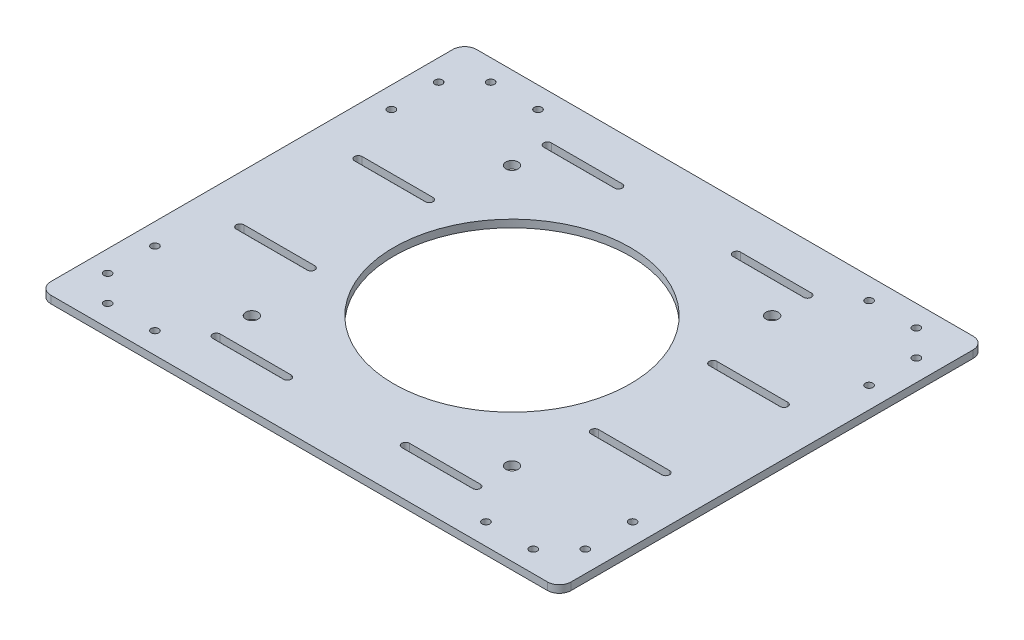
SolidWorks part; units mm, degrees
ref_plane "Front Plane" through (0, 0, 0) normal (0, 0, 1) x (1, 0, 0)
ref_plane "Top Plane" through (0, 0, 0) normal (0, 1, 0) x (1, 0, 0)
ref_plane "Right Plane" through (0, 0, 0) normal (1, 0, 0) x (0, 0, -1)
sketch "Sketch1" plane through (0, 0, 0) normal (0, 1, 0) x (1, 0, 0)
  line L1 (110, -90) -> (-110, -90)
  line L2 (110, -90) -> (110, 90)
  line L3 (110, 90) -> (-110, 90)
  line L4 (-110, -90) -> (-110, 90)
  line L5 (110, -90) -> (-110, 90) construction
  line L6 (110, 90) -> (-110, -90) construction
  point P0 (0, 0)
  dimension "D1" = 220
  dimension "D2" = 180
extrude "Boss-Extrude1" add sketch "Sketch1" along normal blind 3.175
fillet "Fillet1" radius 5 4 edges at (-110, 1.5875, 90) (110, 1.5875, 90) (110, 1.5875, -90) (-110, 1.5875, -90)
sketch "Sketch2" plane through (0, 3.175, 0) normal (0, 1, 0) x (1, 0, 0)
  circle A0 centre (0, 0) radius 69 construction
  circle A1 centre (0, 0) radius 50
  dimension "D1" = 138
  dimension "D2" = 100
extrude "Cut-Extrude1" cut sketch "Sketch2" against normal blind 10
sketch "Sketch4" plane through (0, 3.175, 0) normal (0, 1, 0) x (1, 0, 0)
  line L0 (-90, 81) -> (-70, 81) construction
  line L1 (-90, 84) -> (-70, 84) construction
  line L2 (-90, 78) -> (-70, 78) construction
  line L4 (-110, 85) -> (-110, -85) construction
  line L5 (105, 90) -> (-105, 90) construction
  line L6 (-101, 70) -> (-101, 50) construction
  line L7 (-98, 70) -> (-98, 50) construction
  line L8 (-104, 70) -> (-104, 50) construction
  arc A0 (-90, 84) -> (-90, 78) centre (-90, 81) ccw construction
  arc A1 (-70, 78) -> (-70, 84) centre (-70, 81) ccw construction
  arc A2 (-98, 70) -> (-104, 70) centre (-101, 70) ccw construction
  arc A3 (-104, 50) -> (-98, 50) centre (-101, 50) ccw construction
  point P2 (-80, 81)
  point P13 (-101, 60)
  dimension "D1" = 6
  dimension "D2" = 20
  dimension "D3" = 30
  dimension "D4" = 9
  dimension "D5" = 20
  dimension "D6" = 30
  dimension "D7" = 6
  dimension "D8" = 9
sketch "Sketch5" plane through (0, 3.175, 0) normal (0, 1, 0) x (1, 0, 0)
  circle A0 centre (-70, 81) radius 1.6
  circle A1 centre (-90, 81) radius 1.6
  circle A2 centre (-101, 70) radius 1.6
  circle A3 centre (-101, 50) radius 1.6
  dimension "D1" = 3.2
extrude "Cut-Extrude3" cut sketch "Sketch5" against normal blind 10
mirror "Mirror1" about plane through (0, 0, 0) normal (1, 0, 0) of "Cut-Extrude3"
mirror "Mirror2" about plane through (0, 0, 0) normal (0, 0, 1) of "Mirror1", "Cut-Extrude3"
sketch "Sketch6" plane through (0, 3.175, 0) normal (0, 1, 0) x (1, 0, 0)
  line L1 (55, -55) -> (-55, -55) construction
  line L2 (55, -55) -> (55, 55) construction
  line L3 (55, 55) -> (-55, 55) construction
  line L4 (-55, -55) -> (-55, 55) construction
  line L5 (55, -55) -> (-55, 55) construction
  line L6 (55, 55) -> (-55, -55) construction
  point P0 (0, 0)
  dimension "D1" = 110
  dimension "D2" = 110
sketch "Sketch7" plane through (0, 3.175, 0) normal (0, 1, 0) x (1, 0, 0)
  circle A0 centre (-55, 55) radius 2.6
  circle A1 centre (55, 55) radius 2.6
  circle A2 centre (55, -55) radius 2.6
  circle A3 centre (-55, -55) radius 2.6
  dimension "D1" = 5.2
extrude "Cut-Extrude4" cut sketch "Sketch7" against normal blind 10
sketch "Sketch8" plane through (0, 3.175, 0) normal (0, 1, 0) x (1, 0, 0)
  line L1 (-40, -70) -> (40, -70) construction
  line L2 (-40, -70) -> (-40, 70) construction
  line L3 (-40, 70) -> (40, 70) construction
  line L4 (40, -70) -> (40, 70) construction
  line L5 (-40, -70) -> (40, 70) construction
  line L6 (-40, 70) -> (40, -70) construction
  line L7 (105, 90) -> (-105, 90) construction
  line L8 (-55, 70) -> (-25, 70) construction
  line L9 (-55, 71.6) -> (-25, 71.6)
  line L10 (-55, 68.4) -> (-25, 68.4)
  line L11 (55, 70) -> (25, 70) construction
  line L12 (55, 68.4) -> (25, 68.4)
  line L13 (55, 71.6) -> (25, 71.6)
  arc A1 (-55, 71.6) -> (-55, 68.4) centre (-55, 70) ccw
  arc A2 (-25, 68.4) -> (-25, 71.6) centre (-25, 70) ccw
  arc A3 (55, 68.4) -> (55, 71.6) centre (55, 70) ccw
  arc A4 (25, 71.6) -> (25, 68.4) centre (25, 70) ccw
  point P0 (0, 0)
  point P10 (-40, 70)
  point P17 (40, 70)
  dimension "D2" = 80
  dimension "D1" = 20
  dimension "D3" = 3.2
  dimension "D4" = 30
  dimension "D5" = 30
  dimension "D6" = 3.2
extrude "Cut-Extrude5" cut sketch "Sketch8" against normal blind 10
mirror "Mirror3" about plane through (0, 0, 0) normal (0, 0, 1) of "Cut-Extrude5"
sketch "Sketch9" plane through (0, 3.175, 0) normal (0, 1, 0) x (1, 0, 0)
  line L1 (75, -25) -> (-75, -25) construction
  line L2 (75, -25) -> (75, 25) construction
  line L3 (75, 25) -> (-75, 25) construction
  line L4 (-75, -25) -> (-75, 25) construction
  line L5 (75, -25) -> (-75, 25) construction
  line L6 (75, 25) -> (-75, -25) construction
  point P0 (0, 0)
  dimension "D1" = 150
  dimension "D2" = 50
sketch "Sketch10" plane through (0, 3.175, 0) normal (0, 1, 0) x (1, 0, 0)
  line L0 (-60, 25) -> (-90, 25) construction
  line L1 (-60, 23.4) -> (-90, 23.4)
  line L2 (-60, 26.6) -> (-90, 26.6)
  line L3 (-90, -25) -> (-60, -25) construction
  line L4 (75, -25) -> (-75, -25) construction
  line L5 (-90, -23.4) -> (-60, -23.4)
  line L6 (-90, -26.6) -> (-60, -26.6)
  arc A0 (-60, 23.4) -> (-60, 26.6) centre (-60, 25) ccw
  arc A1 (-90, 26.6) -> (-90, 23.4) centre (-90, 25) ccw
  arc A2 (-90, -23.4) -> (-90, -26.6) centre (-90, -25) ccw
  arc A3 (-60, -26.6) -> (-60, -23.4) centre (-60, -25) ccw
  point P2 (-75, 25)
  point P13 (-75, -25)
  dimension "D1" = 30
  dimension "D2" = 3.2
  dimension "D3" = 3.2
  dimension "D4" = 30
extrude "Cut-Extrude6" cut sketch "Sketch10" against normal blind 10
mirror "Mirror4" about plane through (0, 0, 0) normal (1, 0, 0) of "Cut-Extrude6"
